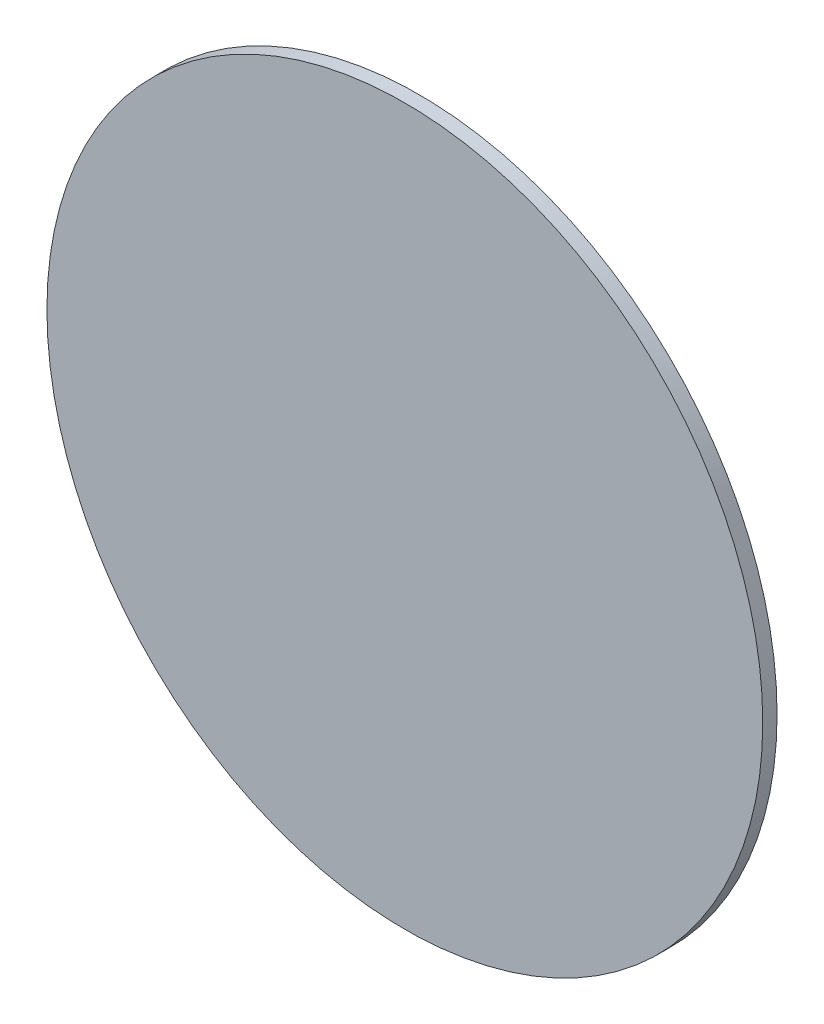
SolidWorks part; units mm, degrees
ref_plane "Front Plane" through (0, 0, 0) normal (0, 0, 1) x (1, 0, 0)
ref_plane "Top Plane" through (0, 0, 0) normal (0, 1, 0) x (1, 0, 0)
ref_plane "Right Plane" through (0, 0, 0) normal (1, 0, 0) x (0, 0, -1)
sketch "Sketch1" plane through (0, 0, 0) normal (0, 0, 1) x (1, 0, 0)
  circle A0 centre (0, 0) radius 12.5
  dimension "D1" = 25
extrude "Boss-Extrude1" add sketch "Sketch1" along normal blind 0.5
